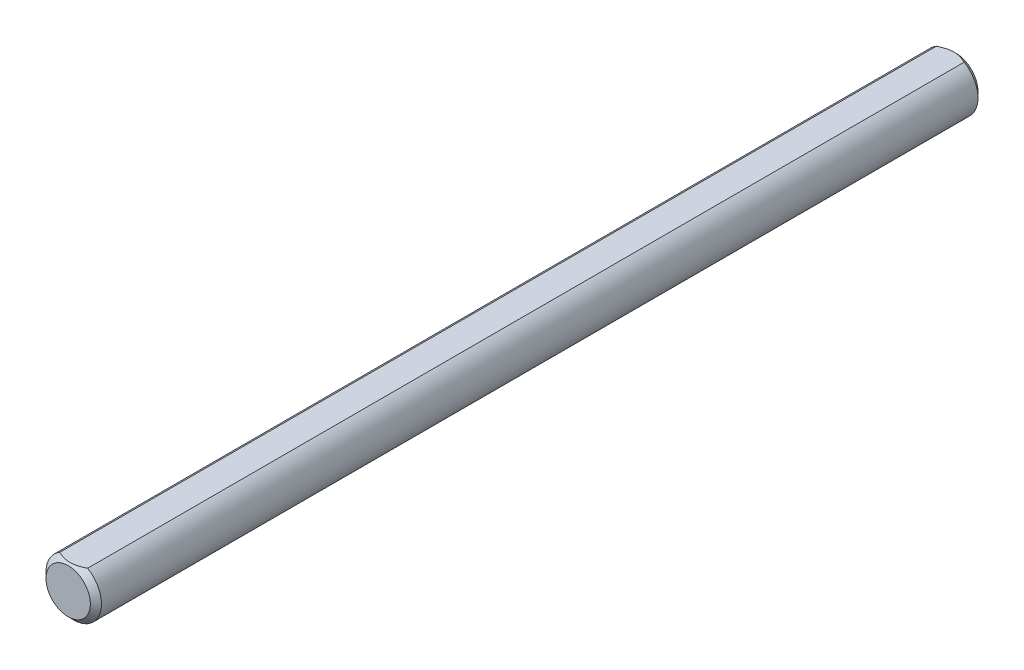
SolidWorks part; units mm, degrees
ref_plane "Front" through (0, 0, 0) normal (0, 0, 1) x (1, 0, 0)
ref_plane "Top" through (0, 0, 0) normal (0, 1, 0) x (1, 0, 0)
ref_plane "Right" through (0, 0, 0) normal (1, 0, 0) x (0, 0, -1)
sketch "Sketch1" plane through (0, 0, 0) normal (0, 0, 1) x (1, 0, 0)
  circle A0 centre (0, 0) radius 3.175
  dimension "D1" = 6.35
extrude "Extrude1" add sketch "Sketch1" along normal mid plane 101.6
chamfer "Chamfer1" distance 0.635 angle 45 2 edges at (3.175, 0, -50.8) (3.175, 0, 50.8)
sketch "Sketch13" plane through (0, 0, 0) normal (0, 0, 1) x (1, 0, 0)
  line L3 (-1.5875, 2.7496) -> (1.5875, 2.7496)
  circle A0 centre (0, 0) radius 3.175 construction
  arc A1 (1.5875, 2.7496) -> (-1.5875, 2.7496) centre (0, 0) ccw
  dimension "D1" = 3.175
extrude "Extrude7" cut sketch "Sketch13" against normal through all and the other way through all
equation "\"D1@Chamfer1\" = \"D1@Sketch1\" * .1"
equation "\"D1@Sketch13\" = \"D1@Sketch1\" * .5"
